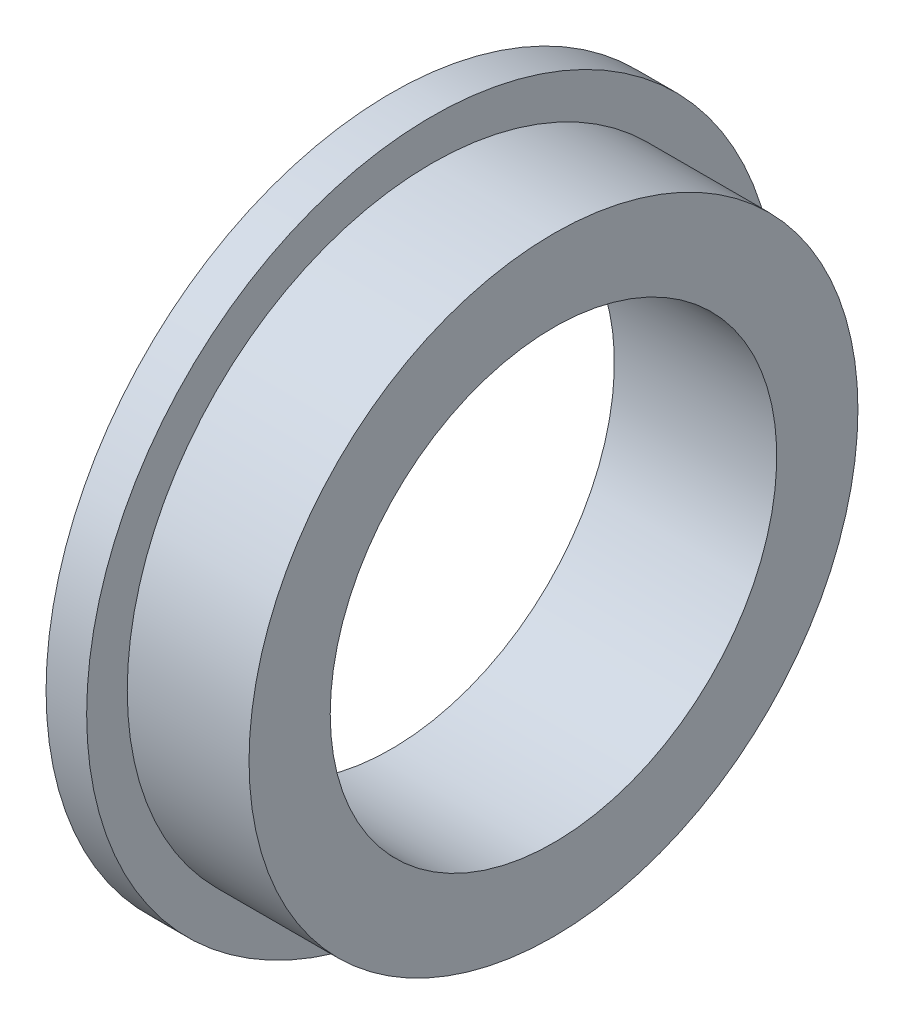
SolidWorks part; units mm, degrees
material "Delrin 2700 NC010, Low Viscosity Acetal Copolymer (SS)"
ref_plane "Front Plane" through (0, 0, 0) normal (0, 0, 1) x (1, 0, 0)
ref_plane "Top Plane" through (0, 0, 0) normal (0, 1, 0) x (1, 0, 0)
ref_plane "Right Plane" through (0, 0, 0) normal (1, 0, 0) x (0, 0, -1)
sketch "Sketch1" plane through (0, 0, 0) normal (0, 0, 1) x (1, 0, 0)
  line L0 (-80.9218, 0) -> (3965.1695, 0) construction
  line L2 (9.525, 17.4625) -> (-3.175, 17.4625)
  line L3 (9.525, 17.4625) -> (9.525, 23.8125)
  line L4 (9.525, 23.8125) -> (-3.175, 23.8125)
  line L5 (-3.175, 17.4625) -> (-3.175, 23.8125)
  line L6 (-3.175, 23.8125) -> (0, 23.8125)
  line L7 (-3.175, 23.8125) -> (-3.175, 26.9875)
  line L8 (-3.175, 26.9875) -> (0, 26.9875)
  line L9 (0, 23.8125) -> (0, 26.9875)
  dimension "D1" = 12.7
  dimension "D2" = 17.4625
  dimension "D3" = 6.35
  dimension "D4" = 3.175
  dimension "D5" = 3.175
revolve "Revolve1" add sketch "Sketch1" angle 360 about L0
equation "\"D2@Sketch1\"=(1.125+.25)/2"
